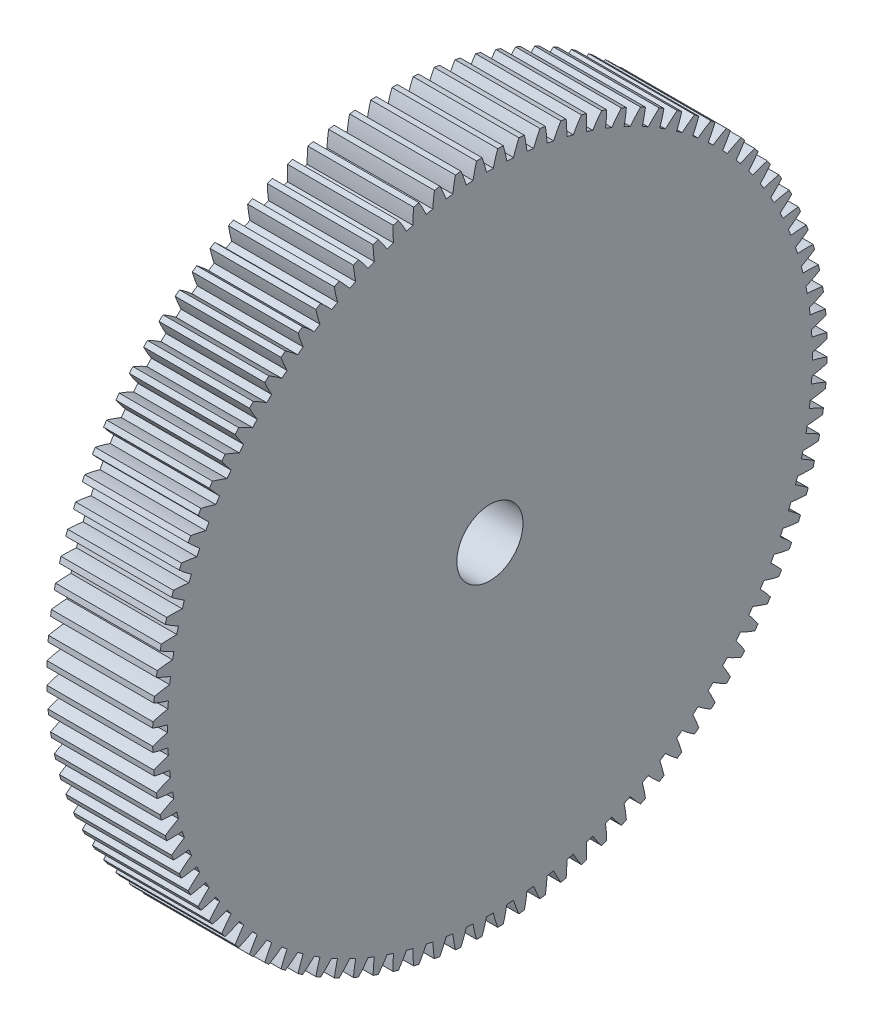
SolidWorks part; units mm, degrees
ref_plane "Plane1" through (0, 0, 0) normal (0, 0, 1) x (1, 0, 0)
ref_plane "Plane2" through (0, 0, 0) normal (0, 1, 0) x (1, 0, 0)
ref_plane "Plane3" through (0, 0, 0) normal (1, 0, 0) x (0, 0, -1)
other "Configuration Table"
sketch "HoldingSke" plane through (0, 0, 0) normal (0, 1, 0) x (1, 0, 0)
  line L0 (0, 0) -> (-0.3473, -1.9696)
  line L1 (-15, 0) -> (100, 0) construction
  line L2 (0, 0) -> (-2.1039, 2.3779)
  line L3 (0, 0) -> (-11.863, 4.5341)
  line L4 (0, 0) -> (-1.4996, 8.5048)
  line L5 (0, 0) -> (-46.8476, -17.4728)
  line L6 (0, 0) -> (-6.6317, -4.4744)
  line L7 (-2.1039, 2.3779) -> (8.6586, 51.2059)
  line L8 (-76.2, 54.61) -> (-75.3, 54.61)
  line L9 (-67.7845, 28.3722) -> (-49.3413, 33.142)
  line L10 (-76.2, 71.12) -> (104.1128, 71.12)
  line L11 (0, 0) -> (-8, 0)
  line L12 (-76.2, 101.6) -> (-76.181, 101.6)
  line L13 (24.9733, 27.94) -> (52.9518, 28.4284)
  line L14 (24.9733, 27.94) -> (24.9743, 27.94)
  line L15 (24.9733, 27.94) -> (100.4006, 29.5858)
  line L16 (-63.627, -0.5) -> (-12.827, -0.5)
  circle A0 centre (0, 0) radius 2.5
  circle A1 centre (0, 0) radius 24.374
  circle A2 centre (0, 0) radius 37.5
  circle A3 centre (0, 0) radius 2.5
  dimension "MHD" = 48.748
  dimension "Hub_dia" = 75
  dimension "Bore" = 5
  dimension "MBD" = 5
  dimension "Num_teeth" = 100
  dimension "Pitch" = 2
  dimension "Overall_len" = 50
  dimension "Show_teeth" = 100
  dimension "Thickness" = 8
  dimension "OAL" = 50.0001
  dimension "T_dim" = 0.9
  dimension "Ap" = 14.5
  dimension "H" = 19.05
  dimension "Pitch_radius" = 180.3128
  dimension "Width" = 8
  dimension "Backlash" = 0.019
  dimension "Addendum_fac" = 1
  dimension "Dedendum_fac" = 1.25
  dimension "Clearance_fac" = 0.25
  dimension "Dedendum_add" = 0.001
  dimension "Module" = 0.5
sketch "BasProSke" plane through (0, 0, 0) normal (0, 1, 0) x (1, 0, 0)
  line L0 (-10, 0) -> (60, 0) construction
  line L1 (0, 0) -> (0, 25.5)
  line L2 (0, 0) -> (8, 0)
  line L3 (8, 0) -> (8, 25.5)
  line L4 (8, 25.5) -> (0, 25.5)
  dimension "Thickness" = 8
  dimension "Diameter" = 51
revolve "Base-Revolve" add sketch "BasProSke" angle 360 about L0
sketch "TooCutSke" plane through (0, 0, 0) normal (1, 0, 0) x (0, 0, -1)
  line L1 (0, 0) -> (0, 107) construction
  line L2 (0, 0) -> (-0.4259, 24.9964) construction
  line L3 (0, 0) -> (-1.5704, 49.9702) construction
  line L4 (-0.4259, 24.9964) -> (-0.7852, 24.9851) construction
  arc A0 (0.2555, 24.3727) -> (-0.2555, 24.3727) centre (0, 0) ccw
  arc A1 (0.6028, 25.5183) -> (-0.6028, 25.5183) centre (0, 0) ccw
  circle A2 centre (0, 0) radius 25 construction
  circle A3 centre (0, 0) radius 24.2037 construction
  arc A4 (-0.2555, 24.3727) -> (-0.6028, 25.5183) centre (-9.9819, 22.0495) ccw
  arc A5 (0.6028, 25.5183) -> (0.2555, 24.3727) centre (9.9819, 22.0495) ccw
  dimension "Root_dia" = 48.748
  dimension "Overcut_dia" = 51.0508
  dimension "Pitch_dia" = 50
  dimension "Base_dia" = 48.4074
  dimension "Flank_rad" = 10
  dimension "Half_ang" = 1.8
  dimension "Half_CT" = 0.3594
extrude "ToothCut" cut sketch "TooCutSke" along normal through all
fillet "Breaks" [suppressed] radius 0.01
fillet "RootFillets" [suppressed] radius 0.126
pattern_circular "TeethCuts" count 100 every 3.6 about axis through (-10, 0, 0) along (1, 0, 0) of "ToothCut", "RootFillets", "Breaks"
sketch "HubNeaOneSke" plane through (0, 0, 0) normal (-1, 0, 0) x (0, 0, 1)
  circle A0 centre (0, 0) radius 24.374
  dimension "Diameter" = 48.748
extrude "HubNearOne" [suppressed] add sketch "HubNeaOneSke" along normal blind 42.0001
sketch "HubNeaBotSke" plane through (0, 0, 0) normal (-1, 0, 0) x (0, 0, 1)
  circle A0 centre (0, 0) radius 24.374
  dimension "Diameter" = 48.748
extrude "HubNearBoth" [suppressed] add sketch "HubNeaBotSke" along normal blind 21
ref_plane "FarPln" through (8, 0, 0) normal (1, 0, 0) x (0, 0, -1)
sketch "HubFarSke" plane through (8, 0, 0) normal (1, 0, 0) x (0, 0, -1)
  circle A0 centre (0, 0) radius 24.374
  dimension "Diameter" = 48.748
extrude "HubFar" [suppressed] add sketch "HubFarSke" along normal blind 21
sketch "BorSke" plane through (0, 0, 0) normal (1, 0, 0) x (0, 0, -1)
  circle A0 centre (0, 0) radius 2.5
  dimension "Diameter" = 5
extrude "Bore" cut sketch "BorSke" along normal mid plane 100.0001
sketch "KeySke" plane through (0, 0, 0) normal (1, 0, 0) x (0, 0, -1)
  line L0 (-1, 0) -> (-1, 3.4)
  line L1 (-1, 3.4) -> (1, 3.4)
  line L2 (1, 3.4) -> (1, 0)
  line L3 (0, 0) -> (0, 34) construction
  line L4 (-1, 0) -> (1, 0)
  dimension "Offset" = 3.4
  dimension "Width" = 2
extrude "Keyway" [suppressed] cut sketch "KeySke" along normal mid plane 100.0001
pattern_circular "Keyway2" [suppressed] count 2 every 90 about axis through (-10, 0, 0) along (1, 0, 0)
equation "' \"Module@HoldingSke\" = 6.35"
equation "' \"Num_teeth@HoldingSke\" = 12"
equation "' \"Ap@HoldingSke\" =  20"
equation "' \"Ap@HoldingSke\" = 20"
equation "' \"Width@HoldingSke\" = 0.5 * 25.4"
equation "' \"Hub_dia@HoldingSke\"= 1 * 25.4"
equation "' \"Hub_dia@HoldingSke\" = 1 * 25.4"
equation "' \"Overall_len@HoldingSke\" = 1.0 * 25.4"
equation "' \"Bore@HoldingSke\" = 0.75 * 25.4"
equation "' \"T_dim@HoldingSke\" = 0.1 * 25.4"
equation "' \"Width@KeySke\" = 0.25 * 25.4"
equation "' \"Show_teeth@HoldingSke\" = 13"
equation "' \"Backlash@HoldingSke\" = 0.009 * 25.4"
equation "' \"Addendum_fac@HoldingSke\" = 1.0"
equation "' \"Dedendum_fac@HoldingSke\" = 1.25"
equation "' \"Dedendum_add@HoldingSke\" = 0.00005 * 25.4"
equation "' \"Clearance_fac@HoldingSke\" = 0.25"
equation "\"Pitch@HoldingSke\" = 1 / \"Module@HoldingSke\""
equation "\"Overcut_dia@TooCutSke\" = (\"Num_teeth@HoldingSke\" + 2 * \"Addendum_fac@HoldingSke\") / \"Pitch@HoldingSke\" + 0.002 * 25.4"
equation "\"Pitch_dia@TooCutSke\" = \"Num_teeth@HoldingSke\" / \"Pitch@HoldingSke\""
equation "\"Base_dia@TooCutSke\" = \"Num_teeth@HoldingSke\" / \"Pitch@HoldingSke\" * cos((\"Ap@HoldingSke\"  * 3.14159265 / 180))"
equation "\"Root_dia@TooCutSke\" = (\"Num_teeth@HoldingSke\" + 2) / \"Pitch@HoldingSke\" - 2 * (\"Addendum_fac@HoldingSke\" + \"Dedendum_fac@HoldingSke\") / \"Pitch@HoldingSke\" - \"Dedendum_add@HoldingSke\" * 2"
equation "\"Half_ang@TooCutSke\" = 180 / \"Num_teeth@HoldingSke\""
equation "\"Half_CT@TooCutSke\" = \"Num_teeth@HoldingSke\" / \"Pitch@HoldingSke\" * sin((3.14159265 / 2 / \"Num_teeth@HoldingSke\")) / 2 - 7 * \"Backlash@HoldingSke\" / 4"
equation "\"Flank_rad@TooCutSke\" = \"Num_teeth@HoldingSke\" / \"Pitch@HoldingSke\" / 5"
equation "\"Radius@RootFillets\" = \"Clearance_fac@HoldingSke\" / \"Pitch@HoldingSke\" + \"Dedendum_add@HoldingSke\""
equation "\"Break_rad@Breaks\" = 0.02 / \"Pitch@HoldingSke\""
equation "\"Thickness@HoldingSke\" = \"Width@HoldingSke\""
equation "\"OAL@HoldingSke\" = \"Thickness@HoldingSke\""
equation "\"MHD@HoldingSke\" = (\"Num_teeth@HoldingSke\" + 2) / \"Pitch@HoldingSke\" - 2 * (\"Addendum_fac@HoldingSke\" + \"Dedendum_fac@HoldingSke\")  / \"Pitch@HoldingSke\" - \"Dedendum_add@HoldingSke\" * 2"
equation "\"MBD@HoldingSke\" = (\"Num_teeth@HoldingSke\" + 2) / \"Pitch@HoldingSke\" - 2 * (\"Addendum_fac@HoldingSke\" + \"Dedendum_fac@HoldingSke\")  / \"Pitch@HoldingSke\" - \"Dedendum_add@HoldingSke\" * 2 - 0.002 * 25.4"
equation "\"MHD@HoldingSke\" = ((sgn( \"MHD@HoldingSke\" - \"Hub_dia@HoldingSke\" )-1)*( \"MHD@HoldingSke\" - \"Hub_dia@HoldingSke\" ))/-2+ \"Hub_dia@HoldingSke\""
equation "\"MBD@HoldingSke\" = ((sgn( \"MBD@HoldingSke\" - \"Bore@HoldingSke\" )-1)*( \"MBD@HoldingSke\" - \"Bore@HoldingSke\" ))/-2+ \"Bore@HoldingSke\""
equation "\"OAL@HoldingSke\" = ((sgn( \"OAL@HoldingSke\" - \"Overall_len@HoldingSke\" )+1)*( \"OAL@HoldingSke\" - \"Overall_len@HoldingSke\" ))/2 + \"Overall_len@HoldingSke\" + 0.000002 * 25.4"
equation "\"Num_teeth@TeethCuts\" = int( \"Show_teeth@HoldingSke\" ) + 1"
equation "\"Num_teeth@TeethCuts\" = ((sgn( \"Num_teeth@TeethCuts\" - \"Num_teeth@HoldingSke\" )-1)*( \"Num_teeth@TeethCuts\" - \"Num_teeth@HoldingSke\" ))/-2+ \"Num_teeth@HoldingSke\""
equation "\"Num_teeth@TeethCuts\" = ((sgn( \"Num_teeth@TeethCuts\" - 2.0)+1)*( \"Num_teeth@TeethCuts\" - 2.0))/2 +2.0"
equation "\"Angle@TeethCuts\" = 360.0 / \"Num_teeth@HoldingSke\""
equation "\"Diameter@BasProSke\" = (\"Num_teeth@HoldingSke\" + 2 * \"Addendum_fac@HoldingSke\") / \"Pitch@HoldingSke\""
equation "\"Thickness@BasProSke\"  = \"Thickness@HoldingSke\""
equation "' \"Fillet_rad@BasProSke\" =  \"Thickness@HoldingSke\" * 0.05"
equation "' \"Fillet_rad@BasProSke\" = \"Thickness@HoldingSke\" * 0.05"
equation "\"MHD@HoldingSke\" = ((sgn( \"MHD@HoldingSke\" - \"Root_dia@TooCutSke\" )-1)*( \"MHD@HoldingSke\" - \"Root_dia@TooCutSke\" ))/-2+ \"Root_dia@TooCutSke\""
equation "\"Diameter@HubNeaOneSke\" = \"MHD@HoldingSke\""
equation "\"Length@HubNearOne\" = \"OAL@HoldingSke\" - \"Thickness@BasProSke\""
equation "\"Diameter@HubNeaBotSke\" = \"MHD@HoldingSke\""
equation "\"Length@HubNearBoth\" = ( \"OAL@HoldingSke\" - \"Thickness@BasProSke\" ) / 2.0"
equation "\"Thickness@FarPln\" = \"Thickness@BasProSke\""
equation "\"Diameter@HubFarSke\" = \"MHD@HoldingSke\""
equation "\"Length@HubFar\" = ( \"OAL@HoldingSke\" - \"Thickness@BasProSke\" ) / 2.0"
equation "\"Diameter@BorSke\" = \"MBD@HoldingSke\""
equation "\"D1@Bore\" = \"OAL@HoldingSke\" * 2.0"
equation "\"D1@Keyway\" = \"OAL@HoldingSke\" * 2.0"
equation "\"Offset@KeySke\" = \"T_dim@HoldingSke\" + \"MBD@HoldingSke\" / 2.0"
